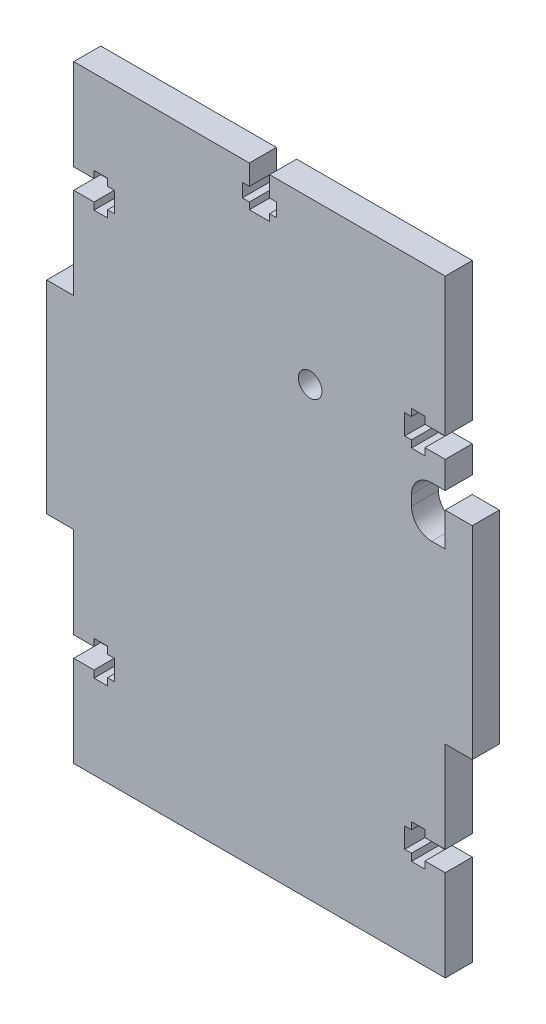
SolidWorks part; units mm, degrees
ref_plane "Спереди" through (0, 0, 0) normal (0, 0, 1) x (1, 0, 0)
ref_plane "Сверху" through (0, 0, 0) normal (0, 1, 0) x (1, 0, 0)
ref_plane "Справа" through (0, 0, 0) normal (1, 0, 0) x (0, 0, -1)
sketch "Эскиз1" plane through (0, 0, 0) normal (0, 0, 1) x (1, 0, 0)
  line L1 (-27.5, -45) -> (27.5, -45)
  line L2 (-27.5, -45) -> (-27.5, 45)
  line L3 (-27.5, 45) -> (27.5, 45)
  line L4 (27.5, -45) -> (27.5, 45)
  line L5 (-27.5, -45) -> (27.5, 45) construction
  line L6 (-27.5, 45) -> (27.5, -45) construction
  line L10 (24.5, -27.45) -> (22.5, -32.55) construction
  line L22 (-21.5, 31.5) -> (-21.5, 28.5) construction
  line L23 (-27.5, 31.5) -> (-21.5, 31.5)
  line L24 (-27.5, 31.5) -> (-27.5, 28.5)
  line L25 (-27.5, 28.5) -> (-21.5, 28.5)
  line L26 (-21.5, 31.5) -> (-21.5, 28.5)
  line L27 (-24.5, 27.45) -> (-22.5, 27.45)
  line L28 (-24.5, 27.45) -> (-24.5, 32.55)
  line L29 (-24.5, 32.55) -> (-22.5, 32.55)
  line L30 (-22.5, 27.45) -> (-22.5, 32.55)
  line L31 (-24.5, 27.45) -> (-22.5, 32.55) construction
  line L32 (-24.5, 32.55) -> (-22.5, 27.45) construction
  line L33 (-21.5, 31.5) -> (-21.5, 28.5) construction
  line L34 (0, -55) -> (0, 55) construction
  line L35 (27.5, 24.5) -> (21.5, 24.5)
  line L36 (31.5, 15) -> (31.5, -15)
  line L37 (27.5, 24.5) -> (27.5, 21.5)
  line L46 (27.5, 21.5) -> (21.5, 21.5)
  line L69 (-27.5, 15) -> (-31.5, 15)
  line L72 (55, 0) -> (-55, 0) construction
  line L73 (24.5, -32.55) -> (22.5, -27.45) construction
  line L74 (21.5, -31.5) -> (21.5, -28.5) construction
  line L75 (27.5, -31.5) -> (21.5, -31.5)
  line L76 (-21.5, -31.5) -> (-21.5, -28.5) construction
  line L77 (-24.5, -32.55) -> (-22.5, -27.45) construction
  line L110 (-24.5, -27.45) -> (-22.5, -32.55) construction
  line L119 (-22.5, -27.45) -> (-22.5, -32.55)
  line L120 (-24.5, -32.55) -> (-22.5, -32.55)
  line L121 (-24.5, -27.45) -> (-24.5, -32.55)
  line L122 (-24.5, -27.45) -> (-22.5, -27.45)
  line L123 (-21.5, -31.5) -> (-21.5, -28.5)
  line L124 (-27.5, -28.5) -> (-21.5, -28.5)
  line L125 (-27.5, -31.5) -> (-27.5, -28.5)
  line L126 (-27.5, -31.5) -> (-21.5, -31.5)
  line L127 (-27.5, 15) -> (-27.5, -15)
  line L128 (-27.5, -15) -> (-31.5, -15)
  line L129 (-31.5, 15) -> (-31.5, -15)
  line L130 (27.5, -15) -> (31.5, -15)
  line L131 (27.5, 15) -> (27.5, -15)
  line L132 (27.5, 15) -> (31.5, 15)
  line L133 (21.5, 24.5) -> (21.5, 21.5)
  line L134 (24.5, 20.45) -> (22.5, 20.45)
  line L135 (24.5, 20.45) -> (24.5, 25.55)
  line L136 (24.5, 25.55) -> (22.5, 25.55)
  line L137 (22.5, 20.45) -> (22.5, 25.55)
  line L138 (24.5, 20.45) -> (22.5, 25.55) construction
  line L139 (24.5, 25.55) -> (22.5, 20.45) construction
  line L140 (27.5, 17.5) -> (22.5, 17.5)
  line L141 (27.5, 17.5) -> (27.5, 10)
  line L142 (27.5, 10) -> (22.5, 10)
  line L143 (22.5, 17.5) -> (22.5, 10)
  line L144 (27.5, -31.5) -> (27.5, -28.5)
  line L145 (27.5, -28.5) -> (21.5, -28.5)
  line L146 (21.5, -31.5) -> (21.5, -28.5)
  line L147 (24.5, -27.45) -> (22.5, -27.45)
  line L148 (24.5, -27.45) -> (24.5, -32.55)
  line L149 (24.5, -32.55) -> (22.5, -32.55)
  line L150 (22.5, -27.45) -> (22.5, -32.55)
  line L152 (-1.5, 39) -> (1.5, 39)
  line L153 (-1.5, 39) -> (-1.5, 45)
  line L154 (-1.5, 45) -> (1.5, 45)
  line L155 (1.5, 39) -> (1.5, 45)
  line L156 (-1.5, 39) -> (1.5, 45) construction
  line L157 (-1.5, 45) -> (1.5, 39) construction
  line L158 (-2.55, 40) -> (2.55, 40)
  line L159 (-2.55, 40) -> (-2.55, 42)
  line L160 (-2.55, 42) -> (2.55, 42)
  line L161 (2.55, 40) -> (2.55, 42)
  line L162 (-2.55, 40) -> (2.55, 42) construction
  line L163 (-2.55, 42) -> (2.55, 40) construction
  circle A0 centre (7.5, 21.1) radius 1.75
  point P0 (0, 0)
  point P14 (-31.5, 0)
  point P16 (-23.5, 30)
  point P24 (-21.5, 30)
  point P27 (-21.5, 30)
  point P34 (21.5, 23)
  point P35 (23.5, 23)
  point P64 (23.5, -30)
  point P65 (-23.5, -30)
  point P70 (0, 42)
  point P75 (3.4796, 41.1623)
  point P76 (0, 41)
  point P81 (-3.2578, 35.1848)
  point P82 (0, 0)
  dimension "D19" = 3.5
  dimension "D1" = 55
  dimension "D2" = 90
  dimension "D3" = 3
  dimension "D4" = 2
  dimension "D5" = 5.1
  dimension "D6" = 3
  dimension "D7" = 6
  dimension "D8" = 30
  dimension "D9" = 4
  dimension "D10" = 8
  dimension "D11" = 3
  dimension "D12" = 6
  dimension "D13" = 3
  dimension "D14" = 5.1
  dimension "D15" = 2
  dimension "D16" = 7.5
  dimension "D17" = 5
  dimension "D18" = 27.5
  dimension "D20" = 23.9
  dimension "D21" = 20
  dimension "D22" = 3
extrude "Бобышка-Вытянуть1" add sketch "Эскиз1" along normal blind 4
fillet "Скругление1" radius 3 2 edges at (22.5, 17.5, 2) (22.5, 10, 2)
